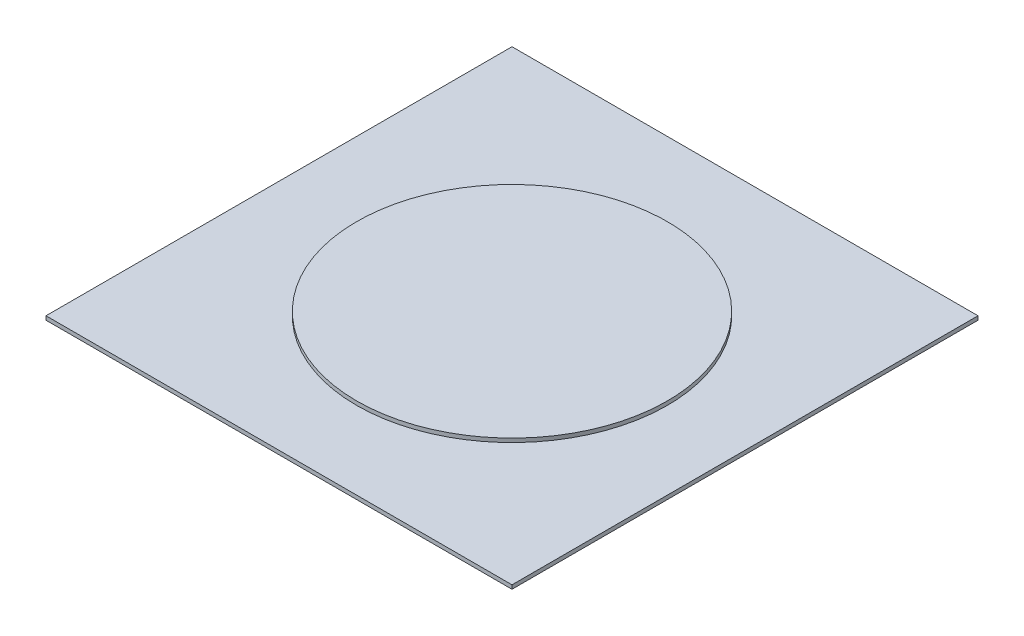
SolidWorks part; units mm, degrees
ref_plane "前视基准面" through (0, 0, 0) normal (0, 0, 1) x (1, 0, 0)
ref_plane "上视基准面" through (0, 0, 0) normal (0, 1, 0) x (1, 0, 0)
ref_plane "右视基准面" through (0, 0, 0) normal (1, 0, 0) x (0, 0, -1)
sketch "草图1" plane through (0, 0, 0) normal (0, 1, 0) x (1, 0, 0)
  line L1 (-60, 60) -> (60, 60)
  line L2 (-60, 60) -> (-60, -60)
  line L3 (-60, -60) -> (60, -60)
  line L4 (60, 60) -> (60, -60)
  line L5 (-60, 60) -> (60, -60) construction
  line L6 (-60, -60) -> (60, 60) construction
  point P0 (0, 0)
  dimension "D1" = 120
extrude "凸台-拉伸1" add sketch "草图1" along normal blind 1
sketch "草图2" plane through (0, 1, 0) normal (0, 1, 0) x (1, 0, 0)
  circle A0 centre (0, 0) radius 40
  dimension "D1" = 80
extrude "凸台-拉伸2" add sketch "草图2" along normal blind 1
